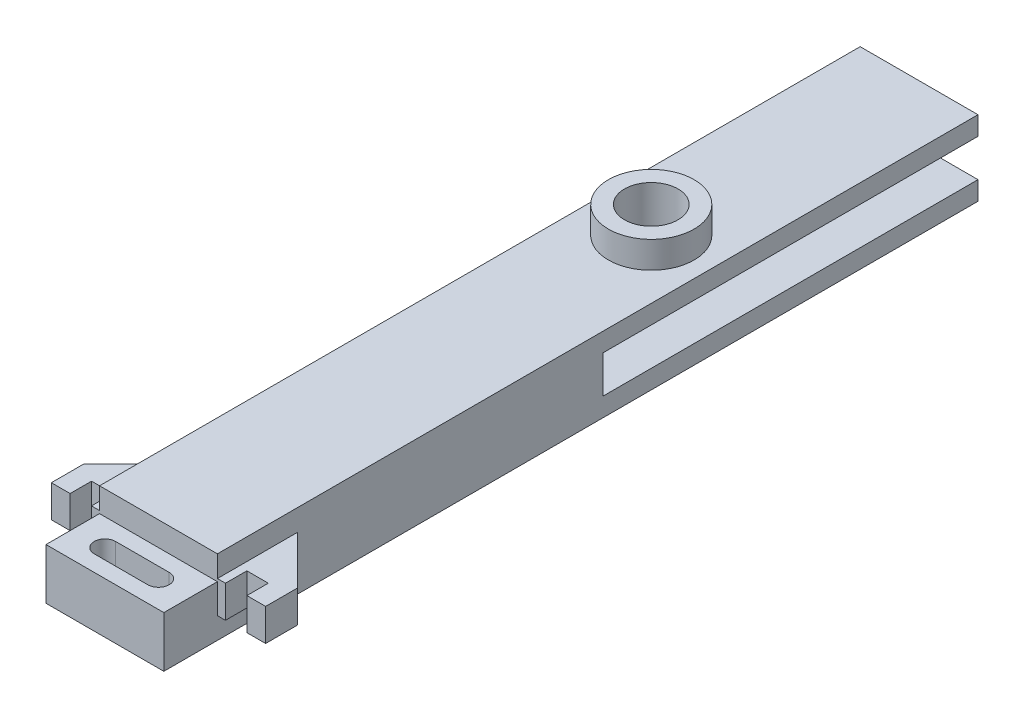
SolidWorks part; units mm, degrees
ref_plane "Front Plane" through (0, 0, 0) normal (0, 0, 1) x (1, 0, 0)
ref_plane "Top Plane" through (0, 0, 0) normal (0, 1, 0) x (1, 0, 0)
ref_plane "Right Plane" through (0, 0, 0) normal (1, 0, 0) x (0, 0, -1)
sketch "Sketch1" plane through (0, 0, 0) normal (0, 1, 0) x (1, 0, 0)
  line L1 (-5.5, 38) -> (5.5, 38)
  line L2 (-5.5, 38) -> (-5.5, -38)
  line L3 (-5.5, -38) -> (5.5, -38)
  line L4 (5.5, 38) -> (5.5, -38)
  line L5 (-5.5, 38) -> (5.5, -38) construction
  line L6 (-5.5, -38) -> (5.5, 38) construction
  point P0 (0, 0)
  dimension "D1" = 76
  dimension "D2" = 11
extrude "Boss-Extrude1" add sketch "Sketch1" along normal blind 7
ref_plane "Plane1" through (0, 0, 0) normal (-1, 0, 0) x (0, 0, 1)
sketch "Sketch3" plane through (0, 0, 0) normal (-1, 0, 0) x (0, 0, 1)
  line L0 (-38, 3.5) -> (28, 3.5)
  line L2 (38, 7) -> (38, 0) construction
  line L3 (-38, 7) -> (-38, 0) construction
  line L4 (31, 0.5) -> (31, 0)
  line L5 (-38, 0) -> (38, 0) construction
  arc A1 (31, 0.5) -> (28, 3.5) centre (28, 0.5) ccw
  point P9 (31, 3.5)
  point P14 (-38, 3.5)
  dimension "D1" = 3
  dimension "D2" = 7
sketch "Sketch4" plane through (0, 0, -38) normal (0, 0, -1) x (-1, 0, 0)
  line L0 (-5.5, 7) -> (-5.5, 0) construction
  line L1 (0, -55.5125) -> (0, 55.5125) construction
  circle A0 centre (0, 3.5) radius 2.5
  point P8 (-5.5, 3.5)
  dimension "D1" = 5
sweep "Cut-Sweep2" cut profiles "Sketch4" path "Sketch3"
sketch "Sketch5" plane through (-5.5, 0, 0) normal (-1, 0, 0) x (0, 0, 1)
  line L0 (38, 7) -> (38, 0) construction
  line L1 (30, 5) -> (33, 5)
  line L2 (30, 5) -> (30, 2)
  line L3 (30, 2) -> (33, 2)
  line L4 (33, 5) -> (33, 2)
  line L5 (30, 5) -> (33, 2) construction
  line L6 (30, 2) -> (33, 5) construction
  point P0 (31.5, 3.5)
  point P7 (38, 3.5)
  point P8 (33, 3.5)
  dimension "D1" = 3
  dimension "D2" = 5
extrude "Boss-Extrude2" add sketch "Sketch5" along normal blind 4.5
ref_plane "Plane2" through (0, 0, 0) normal (-1, 0, 0) x (0, 0, 1)
mirror "Mirror1" about plane through (0, 0, 0) normal (-1, 0, 0) of "Boss-Extrude2"
sketch "Sketch6" plane through (0, 0, 33) normal (0, 0, 1) x (1, 0, 0)
  line L1 (-8.25, 6) -> (-6.25, 6)
  line L2 (-8.25, 6) -> (-8.25, 2)
  line L3 (-8.25, 2) -> (-6.25, 2)
  line L4 (-6.25, 6) -> (-6.25, 2)
  line L5 (-8.25, 6) -> (-6.25, 2) construction
  line L6 (-8.25, 2) -> (-6.25, 6) construction
  line L7 (-10, 2) -> (-5.5, 2) construction
  line L8 (-5.5, 2) -> (-5.5, 5) construction
  point P0 (-7.25, 4)
  dimension "D1" = 0.75
  dimension "D2" = 2
extrude "Cut-Extrude2" cut sketch "Sketch6" against normal offset from surface (2 mm away) 1 up to face at (-7.75, 3.5, 30)
mirror "Mirror2" about plane through (0, 0, 0) normal (-1, 0, 0) of "Cut-Extrude2"
sketch "Sketch7" plane through (0, 5, 0) normal (0, 1, 0) x (1, 0, 0)
  line L0 (-10, -30) -> (-5.5, -25.5)
  line L1 (-5.5, 38) -> (-5.5, -38) construction
  line L2 (-5.5, -25.5) -> (-5.5, -30)
  line L3 (-5.5, -30) -> (-10, -30)
extrude "Boss-Extrude3" add sketch "Sketch7" against normal up to surface (3 mm away) up to face at (-7.5, 2, 31.75)
mirror "Mirror3" about plane through (0, 0, 0) normal (-1, 0, 0) of "Boss-Extrude3"
sketch "Sketch10" plane through (0, 0, -38) normal (0, 0, -1) x (-1, 0, 0)
  line L1 (-5.5, 5.25) -> (5.5, 5.25)
  line L2 (-5.5, 5.25) -> (-5.5, 1.75)
  line L3 (-5.5, 1.75) -> (5.5, 1.75)
  line L4 (5.5, 5.25) -> (5.5, 1.75)
  line L5 (-5.5, 5.25) -> (5.5, 1.75) construction
  line L6 (-5.5, 1.75) -> (5.5, 5.25) construction
  line L8 (-5.5, 7) -> (-5.5, 0) construction
  line L10 (5.5, 7) -> (5.5, 0) construction
  point P0 (0, 3.5)
  point P15 (-5.5, 3.5)
  dimension "D1" = 3.5
  dimension "D2" = 11
extrude "Cut-Extrude5" cut sketch "Sketch10" against normal blind 35
sketch "Sketch11" plane through (0, 7, 0) normal (0, 1, 0) x (1, 0, 0)
  line L0 (5.5, 38) -> (-5.5, 38) construction
  circle A0 centre (0, 13) radius 2.5
  dimension "D1" = 5
  dimension "D2" = 25
extrude "Cut-Extrude6" cut sketch "Sketch11" against normal up to next
sketch "Sketch12" plane through (0, 0, 38) normal (0, 0, 1) x (1, 0, 0)
  line L1 (-5.5, 7) -> (5.5, 7)
  line L2 (-5.5, 7) -> (-5.5, 4.75)
  line L3 (-5.5, 4.75) -> (5.5, 4.75)
  line L4 (5.5, 7) -> (5.5, 4.75)
  line L5 (5.5, 2) -> (5.5, 5) construction
  dimension "D1" = 2.25
  dimension "D2" = 11
extrude "Cut-Extrude9" cut sketch "Sketch12" against normal blind 5
sketch "Sketch14" plane through (0, 4.75, 0) normal (0, 1, 0) x (1, 0, 0)
  line L0 (-2.5, -35.5) -> (2.5, -35.5) construction
  line L1 (-2.5, -34.5) -> (2.5, -34.5)
  line L2 (-2.5, -36.5) -> (2.5, -36.5)
  line L3 (-5.5, -38) -> (5.5, -38) construction
  line L4 (5.5, -33) -> (5.5, -38) construction
  arc A0 (-2.5, -34.5) -> (-2.5, -36.5) centre (-2.5, -35.5) ccw
  arc A1 (2.5, -36.5) -> (2.5, -34.5) centre (2.5, -35.5) ccw
  point P2 (0, -35.5)
  point P9 (0, -38)
  point P13 (5.5, -35.5)
  dimension "D2" = 5
  dimension "D1" = 2
extrude "Cut-Extrude10" cut sketch "Sketch14" against normal up to next
sketch "Sketch15" plane through (0, 7, 0) normal (0, 1, 0) x (1, 0, 0)
  circle A0 centre (0, 13) radius 2.5
  circle A1 centre (0, 13) radius 4
  dimension "D1" = 1.5
extrude "Boss-Extrude4" add sketch "Sketch15" along normal blind 2.5
